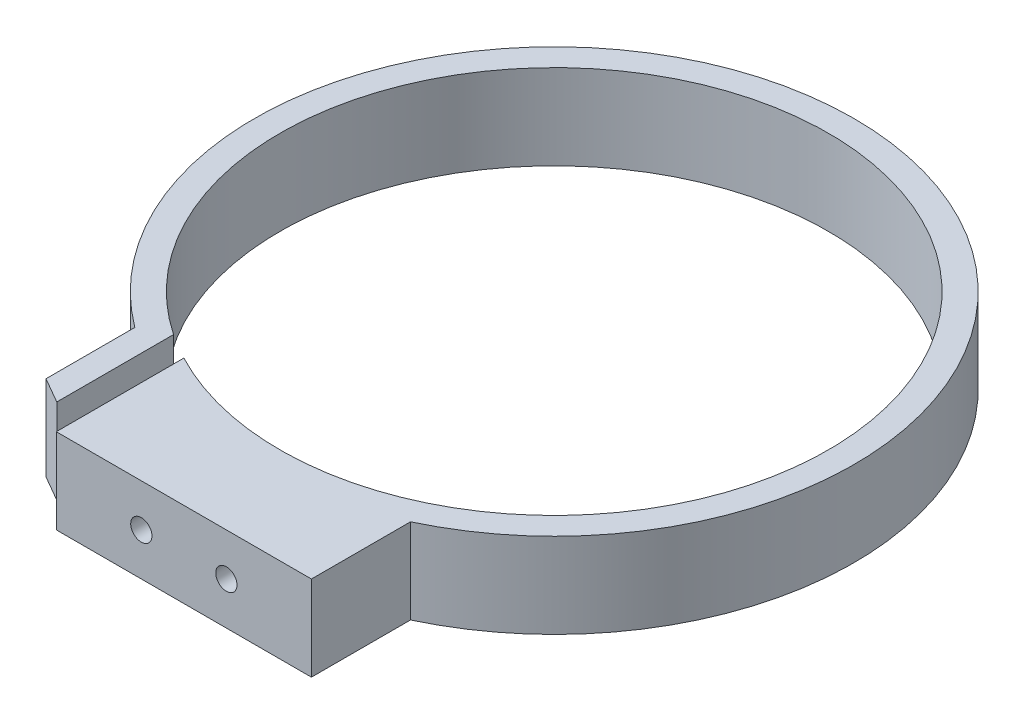
SolidWorks part; units mm, degrees
material "Сплав 2024"
ref_plane "Спереди" through (0, 0, 0) normal (0, 0, 1) x (1, 0, 0)
ref_plane "Сверху" through (0, 0, 0) normal (0, 1, 0) x (1, 0, 0)
ref_plane "Справа" through (0, 0, 0) normal (1, 0, 0) x (0, 0, -1)
sketch "Эскиз1" plane through (0, 0, 0) normal (0, 1, 0) x (1, 0, 0)
  line L0 (-15, -28.5493) -> (-15, -43.5493) construction
  line L1 (-15, -43.5493) -> (15, -43.5493) construction
  line L2 (15, -43.5493) -> (15, -28.5493) construction
  line L3 (15, -28.5493) -> (-15, -28.5493) construction
  line L4 (-15, -31.8993) -> (-15, -43.5493)
  line L5 (-15, -43.5493) -> (15, -43.5493)
  line L6 (15, -43.5493) -> (15, -31.8993)
  circle A0 centre (0, 0) radius 32.25
  arc A1 (15, -31.8993) -> (-15, -31.8993) centre (0, 0) ccw
  circle A3 centre (0, 0) radius 35.25 construction
  point P7 (-15, -31.8993)
  point P10 (15, -31.8993)
  point P12 (35.25, 0)
  dimension "D1" = 64.5
  dimension "D3" = 30
  dimension "D4" = 15
  dimension "D2" = 3
extrude "Бобышка-Вытянуть1" add sketch "Эскиз1" along normal blind 10
ref_plane "Плоскость1" through (15, 0, 0) normal (1, 0, 0) x (0, 0, -1)
ref_plane "Плоскость2" through (-15, 0, 0) normal (1, 0, 0) x (0, 0, -1)
sketch "Эскиз4" plane through (0, 10, 0) normal (0, 1, 0) x (1, 0, 0)
  line L1 (-15, -31.8993) -> (-18, -31.8993)
  line L2 (-15, -31.8993) -> (-15, -23.7125)
  line L3 (-15, -23.7125) -> (-18, -23.7125)
  line L4 (-18, -31.8993) -> (-18, -23.7125)
  dimension "D1" = 3
  dimension "D2" = 8.1867
extrude "Вырез-Вытянуть2" cut sketch "Эскиз4" against normal up to surface (10 mm away) up to face at (0, 0, 20.937)
sketch "Эскиз11" plane through (0, 10, 0) normal (0, 1, 0) x (1, 0, 0)
  line L1 (-18, -26.7593) -> (-21, -26.7593)
  line L2 (-18, -26.7593) -> (-18, -40.4914)
  line L3 (-18, -40.4914) -> (-21, -38.7593)
  line L4 (-21, -26.7593) -> (-21, -38.7593)
  dimension "D1" = 3
  dimension "D2" = 120
  dimension "D3" = 12
extrude "Бобышка-Вытянуть5" add sketch "Эскиз11" against normal up to surface (10 mm away) up to face at (0.037, 0, 13.8254)
sketch "Эскиз12" plane through (-21, 0, 0) normal (-1, 0, 0) x (0, 0, 1)
  line L0 (38.7593, 5) -> (28.3119, 5) construction
  line L1 (38.7593, 0) -> (38.7593, 10) construction
  line L2 (28.3119, 0) -> (28.3119, 10) construction
  line L3 (33.7593, 10) -> (33.7593, 0) construction
  dimension "D1" = 5
hole_wizard "Отверстие с зазором M32" positions "Эскиз14" profile "Эскиз13" hole size "M3" standard "Ansi Metric"
sketch "Эскиз14" plane through (-21, 0, 0) normal (-1, 0, 0) x (0, 0, 1)
  line L1 (33.7593, 10) -> (33.7593, 0) construction
  point P0 (33.7593, 5)
sketch "Эскиз13" plane through (-21, 5, 33.7593) normal (0, 1, 0) x (0, 0, 1)
  line L0 (0, 0) -> (0, 3)
  line L1 (0, 3) -> (1.7, 3)
  line L2 (1.7, 3) -> (1.7, 0)
  line L5 (1.7, 0) -> (0, 0)
  line L11 (0, -6.35) -> (0, 107.95) construction
  dimension "Диаметр сквозного отверстия" = 3.4
  dimension "Глубина сквозного отверстия" = 3
hole_wizard "Отверстие обработанное метчиком M3x0.51" positions "Эскиз16" profile "Эскиз15" tap size "M3x0.5" standard "Ansi Metric"
sketch "Эскиз16" plane through (-15, 0, 0) normal (-1, 0, 0) x (0, 0, 1)
  line L1 (33.7593, 10) -> (33.7593, 0) construction
  line L2 (38.7593, 5) -> (28.3119, 5) construction
  point P0 (33.7593, 5)
sketch "Эскиз15" plane through (-15, 5, 33.7593) normal (0, 1, 0) x (0, 0, 1)
  line L0 (0, 0) -> (0, 9.2511)
  line L1 (0, 9.2511) -> (1.25, 8.5)
  line L2 (1.25, 8.5) -> (1.25, 0)
  line L5 (1.25, 0) -> (0, 0)
  line L10 (0, 9.2511) -> (-1.25, 8.5) construction
  line L11 (0, -6.35) -> (0, 107.95) construction
  dimension "Диаметр сверла" = 2.5
  dimension "Глубина сверла" = 8.5
  dimension "Угол заточки сверла" = 118
cosmetic thread "Отверстие резьбы1" parameters "D1"=6, "D2"=3
sketch "Эскиз17" plane through (0, 0, 43.5493) normal (0, 0, 1) x (1, 0, 0)
  line L0 (-15, 5) -> (15, 5) construction
  line L1 (-15, 10) -> (-15, 0) construction
  line L2 (15, 10) -> (15, 0) construction
  line L3 (-5, 10) -> (-5, 0) construction
  line L4 (-15, 10) -> (15, 10) construction
  line L5 (-15, 0) -> (15, 0) construction
  line L6 (5, 10) -> (5, 0) construction
  line L7 (-15, 10) -> (-15, 0) construction
  dimension "D1" = 10
  dimension "D2" = 30
  dimension "D3" = 10
hole_wizard "Отверстие обработанное метчиком M3x0.52" positions "Эскиз19" profile "Эскиз18" tap size "M3x0.5" standard "Ansi Metric"
sketch "Эскиз19" plane through (0, 0, 43.5493) normal (0, 0, 1) x (1, 0, 0)
  line L0 (-5, 10) -> (-5, 0) construction
  line L1 (5, 10) -> (5, 0) construction
  point P0 (-5, 5)
  point P4 (5, 5)
sketch "Эскиз18" plane through (-5, 5, 43.5493) normal (1, 0, 0) x (0, -1, 0)
  line L0 (0, 0) -> (0, 9.2511)
  line L1 (0, 9.2511) -> (1.25, 8.5)
  line L2 (1.25, 8.5) -> (1.25, 0)
  line L5 (1.25, 0) -> (0, 0)
  line L10 (0, 9.2511) -> (-1.25, 8.5) construction
  line L11 (0, -6.35) -> (0, 107.95) construction
  dimension "Диаметр сверла" = 2.5
  dimension "Глубина сверла" = 8.5
  dimension "Угол заточки сверла" = 118
cosmetic thread "Отверстие резьбы2" parameters "D1"=6, "D2"=3
cosmetic thread "Отверстие резьбы3" parameters "D1"=6, "D2"=3
equation "\"D1@Эскиз17\"=\"D2@Эскиз17\"/3"
equation "\"D3@Эскиз17\"=\"D1@Эскиз17\""
